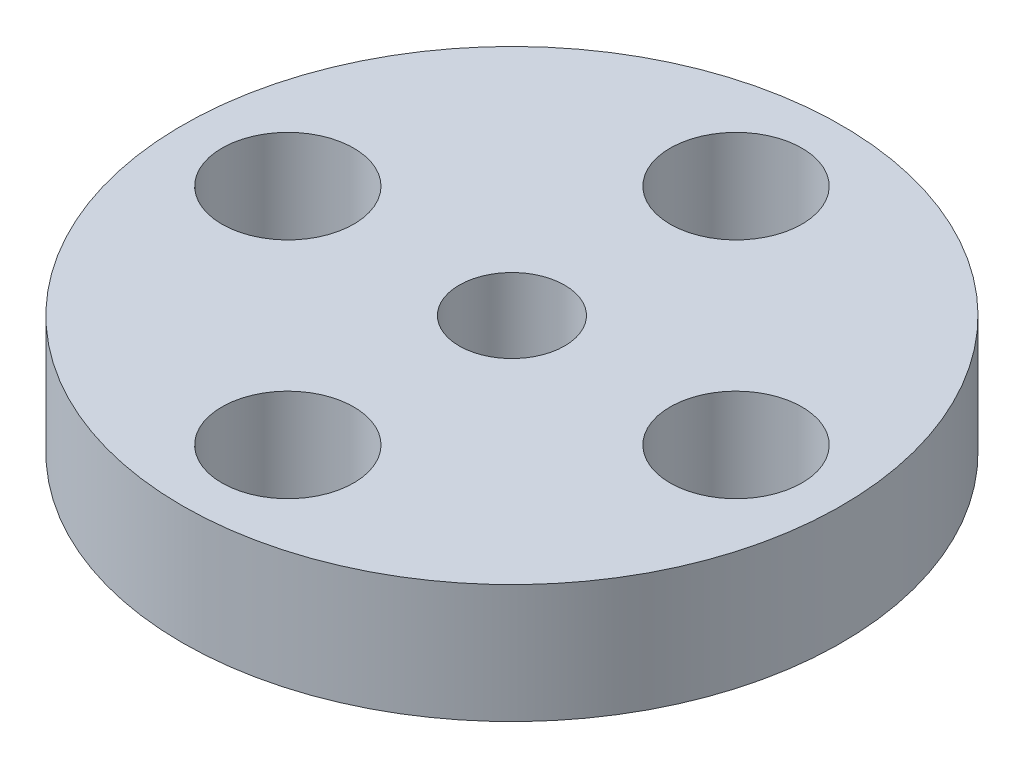
SolidWorks part; units mm, degrees
ref_plane "Front Plane" through (0, 0, 0) normal (0, 0, 1) x (1, 0, 0)
ref_plane "Top Plane" through (0, 0, 0) normal (0, 1, 0) x (1, 0, 0)
ref_plane "Right Plane" through (0, 0, 0) normal (1, 0, 0) x (0, 0, -1)
sketch "Sketch1" plane through (0, 0, 0) normal (0, 1, 0) x (1, 0, 0)
  line L0 (0, 25) -> (0, -25) construction
  line L1 (-25, 0) -> (25, 0) construction
  circle A0 centre (0, 0) radius 25
  circle A1 centre (0, 0) radius 4
  circle A2 centre (0, 0) radius 17 construction
  circle A3 centre (0, 17) radius 5
  circle A10 centre (17, 0) radius 5
  circle A11 centre (0, -17) radius 5
  circle A12 centre (-17, 0) radius 5
  point P20 (2.8467, -2.8467)
  point P28 (0, 0)
  dimension "D1" = 50
  dimension "D2" = 8
  dimension "D3" = 34
  dimension "D4" = 10
  dimension "D6" = 4
extrude "Boss-Extrude1" add sketch "Sketch1" along normal blind 9
sketch "Sketch2" plane through (0, 0, 0) normal (0, -1, 0) x (-1, 0, 0)
  circle A0 centre (0, 0) radius 6
  circle M2 centre (0, 0) radius 4
  dimension "D1" = 12
extrude "Boss-Extrude2" add sketch "Sketch2" along normal blind 1 contours A0 M2
